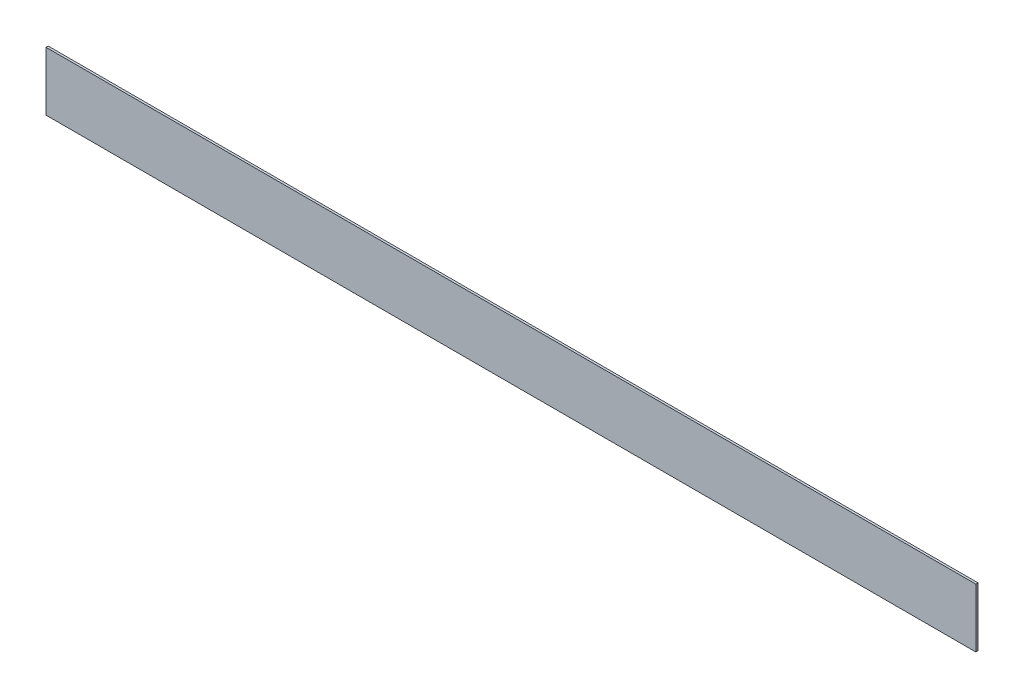
SolidWorks part; units mm, degrees
material "ABS"
ref_plane "Front Plane" through (0, 0, 0) normal (0, 0, 1) x (1, 0, 0)
ref_plane "Top Plane" through (0, 0, 0) normal (0, 1, 0) x (1, 0, 0)
ref_plane "Right Plane" through (0, 0, 0) normal (1, 0, 0) x (0, 0, -1)
sketch "Sketch1" plane through (0, 0, 0) normal (0, 0, 1) x (1, 0, 0)
  line L1 (-213.5, 13.5) -> (213.5, 13.5)
  line L2 (-213.5, 13.5) -> (-213.5, -13.5)
  line L3 (-213.5, -13.5) -> (213.5, -13.5)
  line L4 (213.5, 13.5) -> (213.5, -13.5)
  line L5 (-213.5, 13.5) -> (213.5, -13.5) construction
  line L6 (-213.5, -13.5) -> (213.5, 13.5) construction
  point P0 (0, 0)
  dimension "D1" = 27
  dimension "D2" = 427
extrude "Boss-Extrude1" add sketch "Sketch1" along normal blind 1
